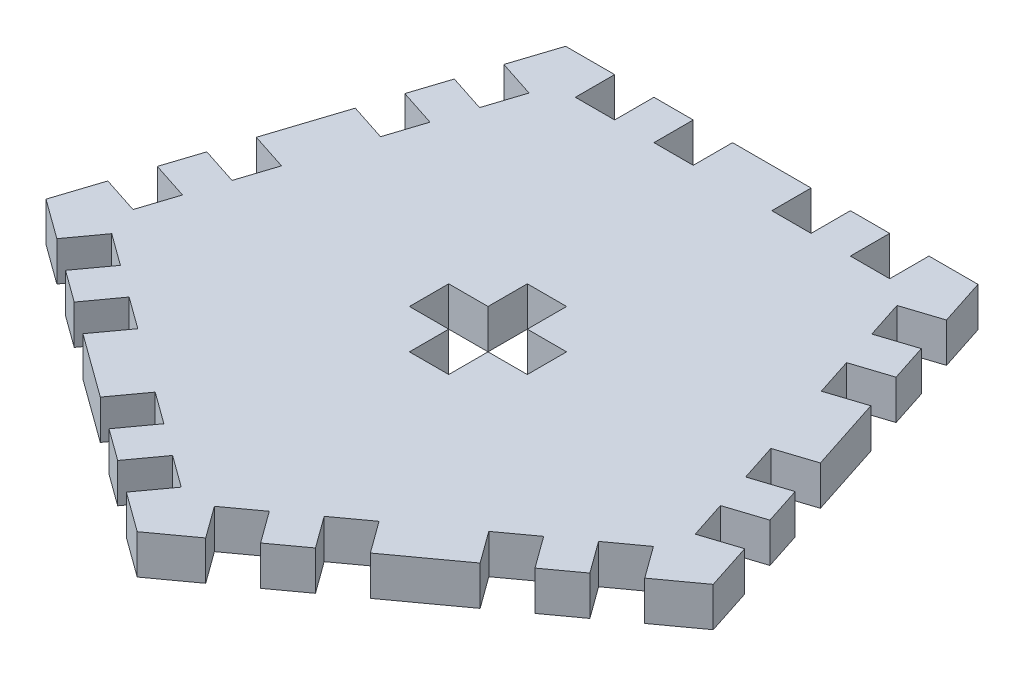
SolidWorks part; units mm, degrees
ref_plane "Front Plane" through (0, 0, 0) normal (0, 0, 1) x (1, 0, 0)
ref_plane "Top Plane" through (0, 0, 0) normal (0, 1, 0) x (1, 0, 0)
ref_plane "Right Plane" through (0, 0, 0) normal (1, 0, 0) x (0, 0, -1)
sketch "Sketch1" plane through (0, 0, 0) normal (0, 1, 0) x (1, 0, 0)
  line L1 (0, -45.3567) -> (43.1368, -14.016)
  line L2 (43.1368, -14.016) -> (26.66, 36.6943)
  line L3 (26.66, 36.6943) -> (-26.66, 36.6943)
  line L4 (-26.66, 36.6943) -> (-43.1368, -14.016)
  line L5 (-43.1368, -14.016) -> (0, -45.3567)
  circle A0 centre (0, 0) radius 36.6943 construction
  dimension "D1" = 53.32
extrude "Boss-Extrude1" add sketch "Sketch1" along normal blind 5.08
sketch "Sketch2" plane through (0, 5.08, 0) normal (0, 1, 0) x (1, 0, 0)
  line L0 (0, 36.6943) -> (0, -45.3567) construction
  line L1 (26.66, 36.6943) -> (-26.66, 36.6943) construction
  line L2 (34.8984, 11.3392) -> (-43.1368, -14.016) construction
  line L3 (43.1368, -14.016) -> (26.66, 36.6943) construction
  line L4 (-43.1368, -14.016) -> (0, -45.3567) construction
  line L5 (-34.8984, 11.3392) -> (43.1368, -14.016) construction
  line L6 (-26.66, 36.6943) -> (-43.1368, -14.016) construction
  line L7 (-20.32, 36.6943) -> (-20.32, 31.6143)
  line L8 (5.08, 36.6943) -> (10.16, 36.6943)
  line L9 (5.08, 36.6943) -> (5.08, 31.6143)
  line L10 (5.08, 31.6143) -> (10.16, 31.6143)
  line L11 (10.16, 36.6943) -> (10.16, 31.6143)
  line L12 (15.24, 36.6943) -> (20.32, 36.6943)
  line L13 (15.24, 36.6943) -> (15.24, 31.6143)
  line L14 (15.24, 31.6143) -> (20.32, 31.6143)
  line L15 (20.32, 36.6943) -> (20.32, 31.6143)
  line L16 (-15.24, 31.6143) -> (-20.32, 31.6143)
  line L17 (-15.24, 36.6943) -> (-15.24, 31.6143)
  line L18 (-15.24, 36.6943) -> (-20.32, 36.6943)
  line L19 (-10.16, 36.6943) -> (-10.16, 31.6143)
  line L20 (-5.08, 31.6143) -> (-10.16, 31.6143)
  line L21 (-5.08, 36.6943) -> (-5.08, 31.6143)
  line L22 (-5.08, 36.6943) -> (-10.16, 36.6943)
  line L23 (28.6192, 30.6646) -> (23.7878, 29.0948)
  line L24 (36.4682, 6.5078) -> (38.038, 1.6764)
  line L25 (36.4682, 6.5078) -> (31.6368, 4.938)
  line L26 (31.6368, 4.938) -> (33.2066, 0.1066)
  line L27 (38.038, 1.6764) -> (33.2066, 0.1066)
  line L28 (39.6078, -3.1549) -> (41.1776, -7.9863)
  line L29 (39.6078, -3.1549) -> (34.7764, -4.7247)
  line L30 (34.7764, -4.7247) -> (36.3463, -9.5561)
  line L31 (41.1776, -7.9863) -> (36.3463, -9.5561)
  line L32 (25.3576, 24.2635) -> (23.7878, 29.0948)
  line L33 (30.189, 25.8333) -> (25.3576, 24.2635)
  line L34 (30.189, 25.8333) -> (28.6192, 30.6646)
  line L35 (31.7588, 21.0019) -> (26.9274, 19.4321)
  line L36 (28.4972, 14.6007) -> (26.9274, 19.4321)
  line L37 (33.3286, 16.1705) -> (28.4972, 14.6007)
  line L38 (33.3286, 16.1705) -> (31.7588, 21.0019)
  line L39 (38.0076, -17.7425) -> (35.0217, -13.6327)
  line L40 (17.4586, -32.6723) -> (13.3488, -35.6582)
  line L41 (17.4586, -32.6723) -> (14.4726, -28.5625)
  line L42 (14.4726, -28.5625) -> (10.3628, -31.5484)
  line L43 (13.3488, -35.6582) -> (10.3628, -31.5484)
  line L44 (9.239, -38.6442) -> (5.1292, -41.6301)
  line L45 (9.239, -38.6442) -> (6.253, -34.5344)
  line L46 (6.253, -34.5344) -> (2.1432, -37.5203)
  line L47 (5.1292, -41.6301) -> (2.1432, -37.5203)
  line L48 (30.9119, -16.6187) -> (35.0217, -13.6327)
  line L49 (33.8978, -20.7285) -> (30.9119, -16.6187)
  line L50 (33.8978, -20.7285) -> (38.0076, -17.7425)
  line L51 (29.788, -23.7144) -> (26.8021, -19.6046)
  line L52 (22.6923, -22.5906) -> (26.8021, -19.6046)
  line L53 (25.6782, -26.7004) -> (22.6923, -22.5906)
  line L54 (25.6782, -26.7004) -> (29.788, -23.7144)
  line L55 (-5.1292, -41.6301) -> (-2.1432, -37.5203)
  line L56 (-25.6782, -26.7004) -> (-29.788, -23.7144)
  line L57 (-25.6782, -26.7004) -> (-22.6923, -22.5906)
  line L58 (-22.6923, -22.5906) -> (-26.8021, -19.6046)
  line L59 (-29.788, -23.7144) -> (-26.8021, -19.6046)
  line L60 (-33.8978, -20.7285) -> (-38.0076, -17.7425)
  line L61 (-33.8978, -20.7285) -> (-30.9119, -16.6187)
  line L62 (-30.9119, -16.6187) -> (-35.0217, -13.6327)
  line L63 (-38.0076, -17.7425) -> (-35.0217, -13.6327)
  line L64 (-6.253, -34.5344) -> (-2.1432, -37.5203)
  line L65 (-9.239, -38.6442) -> (-6.253, -34.5344)
  line L66 (-9.239, -38.6442) -> (-5.1292, -41.6301)
  line L67 (-13.3488, -35.6582) -> (-10.3628, -31.5484)
  line L68 (-14.4726, -28.5625) -> (-10.3628, -31.5484)
  line L69 (-17.4586, -32.6723) -> (-14.4726, -28.5625)
  line L70 (-17.4586, -32.6723) -> (-13.3488, -35.6582)
  line L71 (-41.1776, -7.9863) -> (-36.3463, -9.5561)
  line L72 (-33.3286, 16.1705) -> (-31.7588, 21.0019)
  line L73 (-33.3286, 16.1705) -> (-28.4972, 14.6007)
  line L74 (-28.4972, 14.6007) -> (-26.9274, 19.4321)
  line L75 (-31.7588, 21.0019) -> (-26.9274, 19.4321)
  line L76 (-30.189, 25.8333) -> (-28.6192, 30.6646)
  line L77 (-30.189, 25.8333) -> (-25.3576, 24.2635)
  line L78 (-25.3576, 24.2635) -> (-23.7878, 29.0948)
  line L79 (-28.6192, 30.6646) -> (-23.7878, 29.0948)
  line L80 (-34.7764, -4.7247) -> (-36.3463, -9.5561)
  line L81 (-39.6078, -3.1549) -> (-34.7764, -4.7247)
  line L82 (-39.6078, -3.1549) -> (-41.1776, -7.9863)
  line L83 (-38.038, 1.6764) -> (-33.2066, 0.1066)
  line L84 (-31.6368, 4.938) -> (-33.2066, 0.1066)
  line L85 (-36.4682, 6.5078) -> (-31.6368, 4.938)
  line L86 (-36.4682, 6.5078) -> (-38.038, 1.6764)
  point P99 (0, 0)
  dimension "D1" = 5.08
  dimension "D2" = 5.08
  dimension "D3" = 5.08
  dimension "D4" = 5.08
  dimension "D5" = 5.08
  dimension "D6" = 5.08
  dimension "D7" = 5
extrude "Cut-Extrude1" cut sketch "Sketch2" against normal blind 5.08
sketch "Sketch3" plane through (0, 5.08, 0) normal (0, 1, 0) x (1, 0, 0)
  line L0 (0, 36.6943) -> (0, -45.3567) construction
  line L1 (5.08, 36.6943) -> (-5.08, 36.6943) construction
  line L2 (-34.8984, 11.3392) -> (43.1368, -14.016) construction
  line L3 (-33.3286, 16.1705) -> (-36.4682, 6.5078) construction
  line L4 (34.8984, 11.3392) -> (-43.1368, -14.016) construction
  line L5 (36.4682, 6.5078) -> (33.3286, 16.1705) construction
  line L6 (-50.4032, 0) -> (64.0141, 0) construction
  line L7 (0, 7.62) -> (2.54, 7.62)
  line L8 (2.54, 7.62) -> (2.54, 2.54)
  line L9 (2.54, 2.54) -> (7.62, 2.54)
  line L10 (7.62, 2.54) -> (7.62, 0)
  line L11 (7.62, 0) -> (7.62, -2.54)
  line L12 (7.62, -2.54) -> (2.54, -2.54)
  line L13 (2.54, -2.54) -> (2.54, -7.62)
  line L14 (2.54, -7.62) -> (0, -7.62)
  line L15 (0, -7.62) -> (-2.54, -7.62)
  line L16 (-2.54, -7.62) -> (-2.54, -2.54)
  line L17 (-2.54, -2.54) -> (-7.62, -2.54)
  line L18 (-7.62, -2.54) -> (-7.62, 0)
  line L19 (-7.62, 0) -> (-7.62, 2.54)
  line L20 (-7.62, 2.54) -> (-2.54, 2.54)
  line L21 (-2.54, 2.54) -> (-2.54, 7.62)
  line L22 (-2.54, 7.62) -> (0, 7.62)
  point P41 (0, 0)
  dimension "D1" = 2.54
  dimension "D2" = 2.54
  dimension "D3" = 5.08
  dimension "D4" = 5.08
  dimension "D5" = 4
extrude "Cut-Extrude2" cut sketch "Sketch3" against normal blind 5.08
